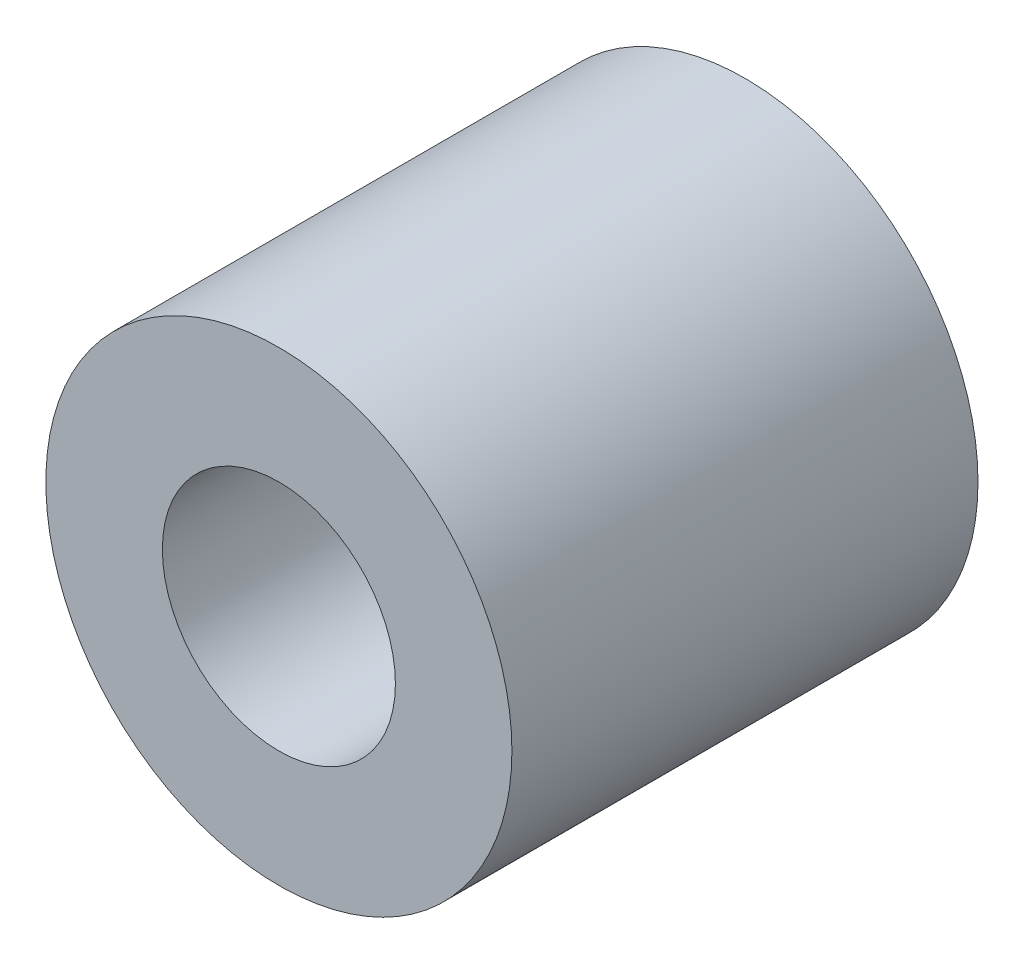
SolidWorks part; units mm, degrees
ref_plane "Front Plane" through (0, 0, 0) normal (0, 0, 1) x (1, 0, 0)
ref_plane "Top Plane" through (0, 0, 0) normal (0, 1, 0) x (1, 0, 0)
ref_plane "Right Plane" through (0, 0, 0) normal (1, 0, 0) x (0, 0, -1)
sketch "Sketch1" plane through (0, 0, 0) normal (0, 0, 1) x (1, 0, 0)
  circle A0 centre (0, 0) radius 6.35
  dimension "D1" = 12.7
extrude "Boss-Extrude1" add sketch "Sketch1" along normal blind 12.7
sketch "Sketch2" plane through (0, 0, 12.7) normal (0, 0, 1) x (1, 0, 0)
  circle A0 centre (0, 0) radius 3.175
  dimension "D1" = 6.35
extrude "Cut-Extrude1" cut sketch "Sketch2" against normal blind 12.7
